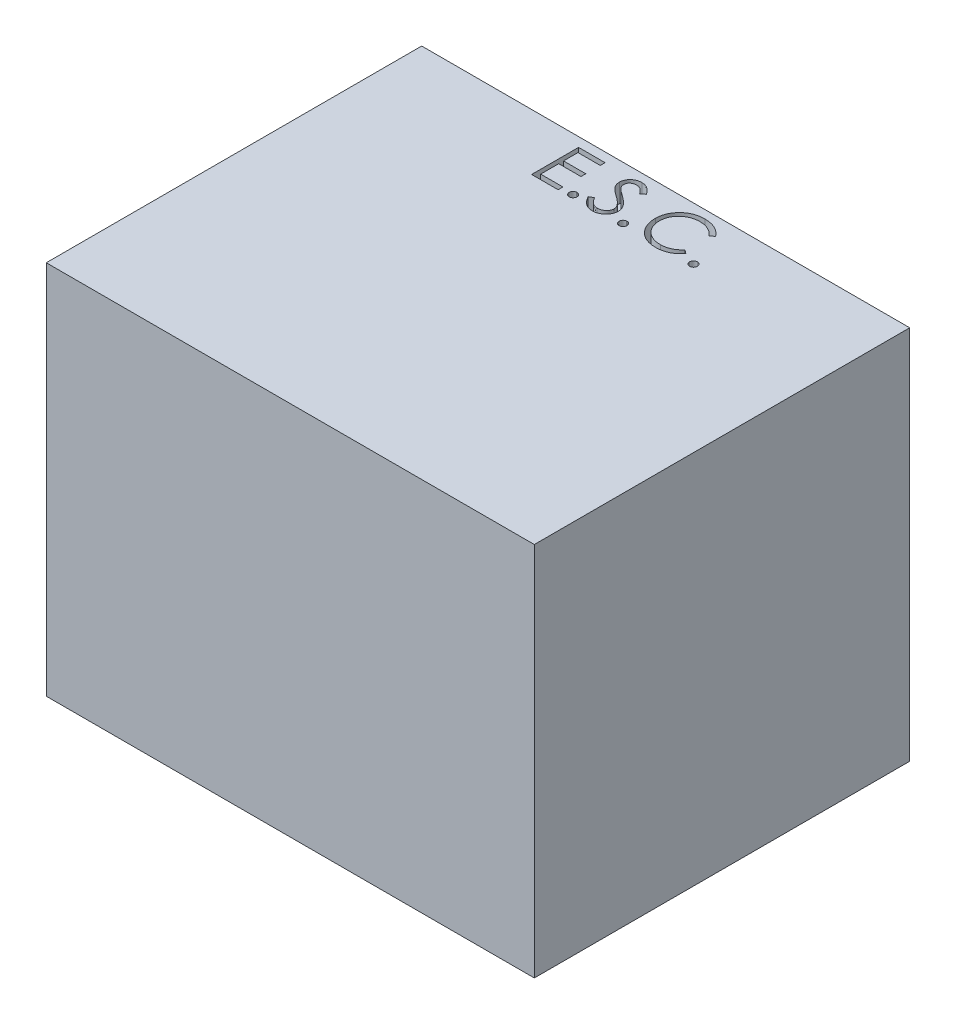
SolidWorks part; units mm, degrees
ref_plane "Front Plane" through (0, 0, 0) normal (0, 0, 1) x (1, 0, 0)
ref_plane "Top Plane" through (0, 0, 0) normal (0, 1, 0) x (1, 0, 0)
ref_plane "Right Plane" through (0, 0, 0) normal (1, 0, 0) x (0, 0, -1)
sketch "Sketch1" plane through (0, 0, 0) normal (1, 0, 0) x (0, 0, -1)
  line L1 (0, 0) -> (25.4, 0)
  line L2 (0, 0) -> (0, 25.4)
  line L3 (0, 25.4) -> (25.4, 25.4)
  line L4 (25.4, 0) -> (25.4, 25.4)
  dimension "D1" = 25.4
  dimension "D2" = 25.4
extrude "Extrude1" add sketch "Sketch1" along normal mid plane 33.02
sketch "Sketch2" plane through (0, 25.4, 0) normal (0, 1, 0) x (1, 0, 0)
  text T0 "E.S.C."
extrude "Extrude2" cut sketch "Sketch2" against normal blind 1.27
